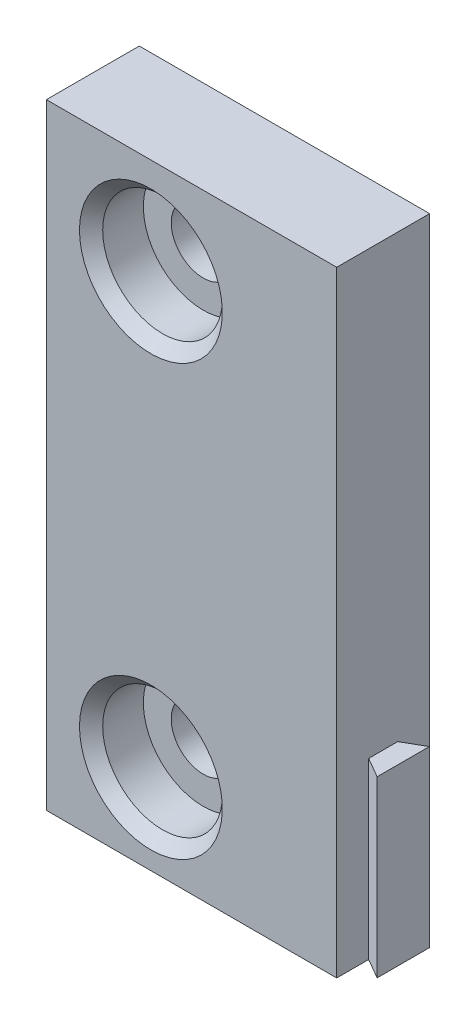
SolidWorks part; units mm, degrees
ref_plane "Front Plane" through (0, 0, 0) normal (0, 0, 1) x (1, 0, 0)
ref_plane "Top Plane" through (0, 0, 0) normal (0, 1, 0) x (1, 0, 0)
ref_plane "Right Plane" through (0, 0, 0) normal (1, 0, 0) x (0, 0, -1)
sketch "Sketch2" plane through (0, 0, 0) normal (0, 0, 1) x (1, 0, 0)
  line L1 (0, 0) -> (25, 0)
  line L2 (0, 0) -> (0, 53)
  line L3 (0, 53) -> (25, 53)
  line L4 (25, 0) -> (25, 53)
  line L5 (0, 26.2) -> (42.3407, 26.2) construction
  circle A0 centre (9, 44.7) radius 2.75
  circle A1 centre (9, 7.7) radius 2.75
  point P9 (8.4768, 44.7)
  point P10 (0, 0)
  dimension "D3" = 5.5
  dimension "D1" = 53
  dimension "D2" = 25
  dimension "D4" = 18.5
  dimension "D5" = 18.5
  dimension "D6" = 26.2
  dimension "D7" = 9
extrude "Boss-Extrude1" add sketch "Sketch2" along normal blind 8
sketch "Sketch3" plane through (0, 0, 0) normal (0, -1, 0) x (1, 0, 0)
  line L0 (25, 2.75) -> (26.7321, 1.75)
  line L1 (26.7321, 1.75) -> (26.7321, 6.25)
  line L2 (26.7321, 6.25) -> (25, 5.25)
  line L3 (25, 8) -> (25, 0) construction
  line L4 (25, 2.75) -> (25, 5.25)
  point P11 (25, 4)
  point P12 (25, 4)
  dimension "D1" = 60
  dimension "D2" = 60
  dimension "D3" = 4.5
  dimension "D4" = 2.5
extrude "Boss-Extrude2" add sketch "Sketch3" against normal blind 15
sketch "Sketch4" plane through (0, 0, 8) normal (0, 0, 1) x (1, 0, 0)
  circle A0 centre (9, 44.7) radius 5.15
  circle A1 centre (9, 7.7) radius 5.15
  dimension "D1" = 10.3
extrude "Cut-Extrude1" cut sketch "Sketch4" against normal blind 4.5
chamfer "Chamfer1" distance 1 angle 45 2 edges at (14.15, 44.7, 8) (14.15, 7.7, 8)
equation "\"D5@Sketch2\"=(11+25)/2 +.5"
equation "\"D4@Sketch2\"=\"D5@Sketch2\""
